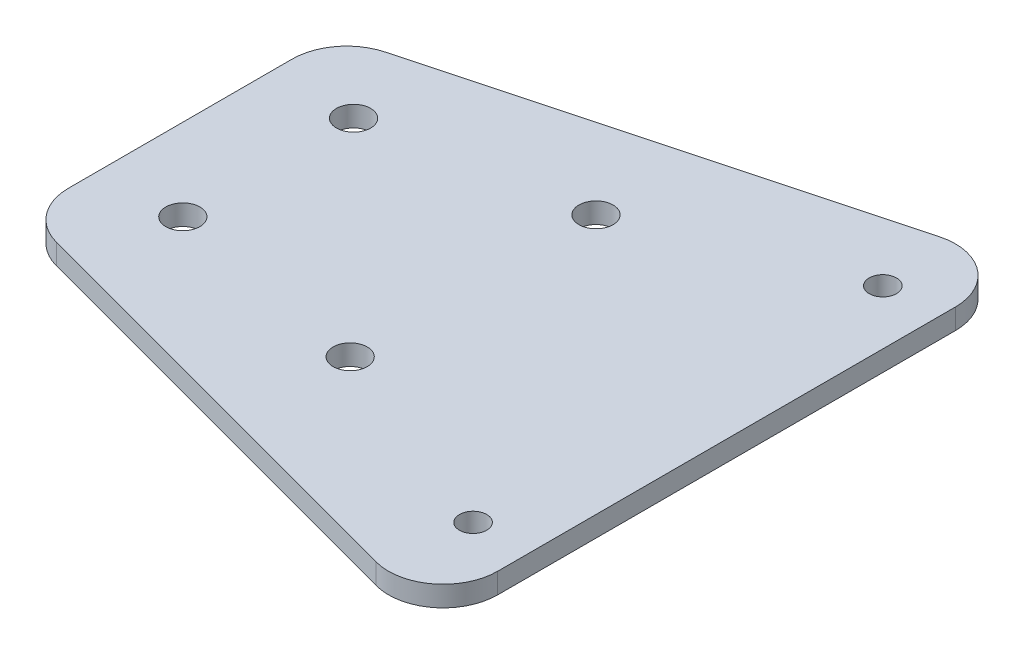
SolidWorks part; units mm, degrees
ref_plane "Front Plane" through (0, 0, 0) normal (0, 0, 1) x (1, 0, 0)
ref_plane "Top Plane" through (0, 0, 0) normal (0, 1, 0) x (1, 0, 0)
ref_plane "Right Plane" through (0, 0, 0) normal (1, 0, 0) x (0, 0, -1)
sketch "Sketch2" plane through (0, 0, 0) normal (0, 1, 0) x (1, 0, 0)
  line L0 (-41.4205, -12.3427) -> (-41.4205, 20.3806)
  line L1 (-35.4914, 28.108) -> (28.5086, 45.26)
  line L2 (38.5795, 37.5326) -> (38.5795, -29.4947)
  line L5 (-41.4205, 4.019) -> (38.5795, 4.019) construction
  line L6 (-35.4914, -20.07) -> (28.5086, -37.222)
  arc A0 (-41.4205, 20.3806) -> (-35.4914, 28.108) centre (-33.4205, 20.3806) cw
  arc A1 (28.5086, 45.26) -> (38.5795, 37.5326) centre (30.5795, 37.5326) cw
  arc A2 (28.5086, -37.222) -> (38.5795, -29.4947) centre (30.5795, -29.4947) ccw
  arc A3 (-41.4205, -12.3427) -> (-35.4914, -20.07) centre (-33.4205, -12.3427) ccw
  point P2 (38.608, 4.019)
  point P4 (0, 0)
  point P5 (0, 0)
  point P7 (-19.2639, -14.3182)
  point P8 (-41.1648, 4.019)
  point P9 (0, 0)
  point P10 (-41.1648, 4.5206)
  point P13 (-41.4205, 26.519)
  point P16 (38.5795, 47.959)
  dimension "D4" = 8
  dimension "D5" = 8
  dimension "D6" = 8
  dimension "D1" = 22.5
  dimension "D2" = 80
  dimension "D3" = 43.94
extrude "Boss-Extrude1" add sketch "Sketch2" along normal mid plane 3
sketch "Sketch3" plane through (0, 1.5, 0) normal (0, 1, 0) x (1, 0, 0)
  line L0 (-41.4205, 4.8942) -> (38.5795, 4.8942) construction
  line L1 (-41.4205, 20.3806) -> (-41.4205, -12.3427) construction
  line L2 (38.5795, -29.4947) -> (38.5795, 37.5326) construction
  circle A0 centre (30.5795, 34.8942) radius 2
  circle A1 centre (0.5795, 22.8942) radius 2.5
  circle A2 centre (-29.4205, 17.3942) radius 2.5
  circle A3 centre (30.5795, -25.1058) radius 2
  circle A4 centre (0.5795, -13.1058) radius 2.5
  circle A5 centre (-29.4205, -7.6058) radius 2.5
  point P12 (0, 0)
  point P13 (0, 0)
  point P14 (-40.3665, 14.9589)
  point P15 (0, 0)
  point P16 (0, 0)
  dimension "D1" = 5
  dimension "D2" = 5
  dimension "D3" = 4
  dimension "D4" = 30
  dimension "D5" = 8
  dimension "D6" = 12.5
  dimension "D7" = 12
  dimension "D8" = 38
  dimension "D9" = 18
extrude "Cut-Extrude1" cut sketch "Sketch3" against normal blind 3
